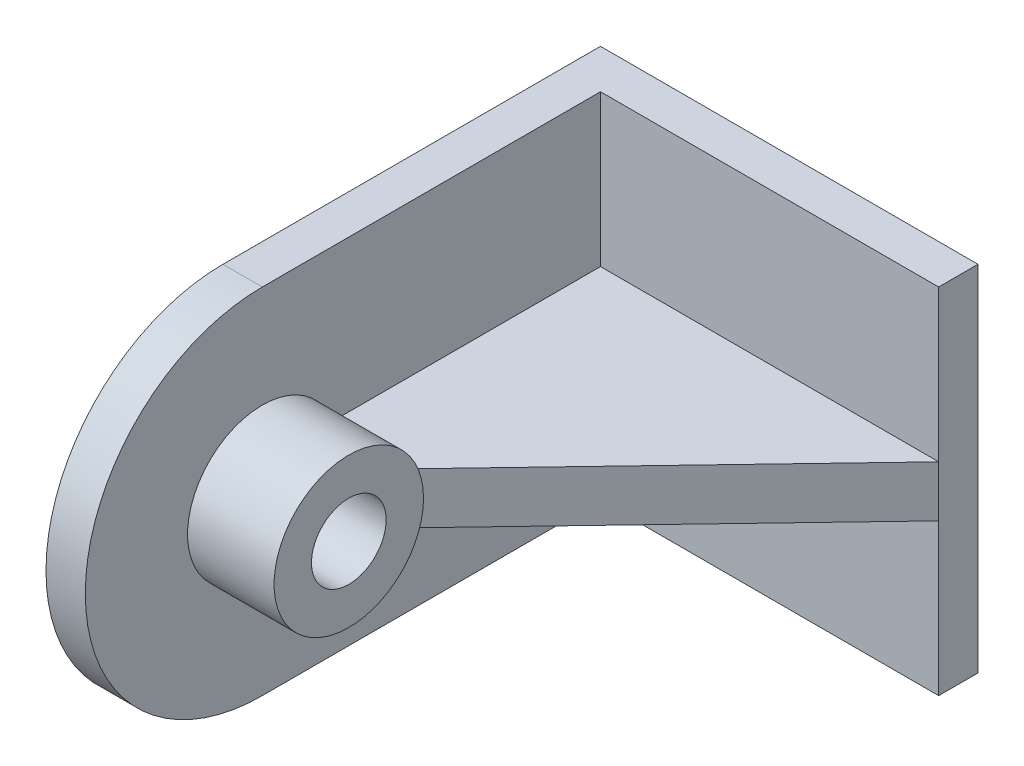
SolidWorks part; units mm, degrees
ref_plane "Front Plane" through (0, 0, 0) normal (1, 0, 0) x (0, 1, 0)
ref_plane "Top Plane" through (0, 0, 0) normal (0, 0, 1) x (0, 1, 0)
ref_plane "Right Plane" through (0, 0, 0) normal (0, 1, 0) x (-1, 0, 0)
sketch "Sketch1" plane through (0, 0, 0) normal (0, 0, 1) x (0, 1, 0)
  line L1 (-45, 48) -> (45, 48)
  line L2 (-45, 48) -> (-45, -48)
  line L3 (-45, -48) -> (45, -48)
  line L4 (45, 48) -> (45, -48)
  line L5 (-45, 48) -> (45, -48) construction
  line L6 (-45, -48) -> (45, 48) construction
  point P0 (0, 0)
  dimension "D1" = 90
  dimension "D2" = 96
extrude "Boss-Extrude1" add sketch "Sketch1" along normal blind 10
sketch "Sketch2" plane through (-48, 0, 0) normal (-1, 0, 0) x (0, -1, 0)
  line L0 (-45, 0) -> (-45, 96)
  line L1 (45, 96) -> (45, 0)
  line L2 (0, 0) -> (0, 84.8091) construction
  line L3 (-45, 0) -> (45, 0)
  arc A0 (-45, 96) -> (45, 96) centre (0, 96) cw
  dimension "D1" = 45
  dimension "D2" = 96
extrude "Boss-Extrude2" add sketch "Sketch2" against normal blind 10
sketch "Sketch3" plane through (-38, 0, 0) normal (1, 0, 0) x (0, 1, 0)
  circle A0 centre (0, 96) radius 19
  circle A1 centre (0, 96) radius 9.5
  dimension "D1" = 38
  dimension "D2" = 19
extrude "Boss-Extrude3" add sketch "Sketch3" along normal blind 22
sketch "Sketch4" plane through (0, 0, 0) normal (0, 1, 0) x (-1, 0, 0)
  line L0 (-48, 10) -> (16, 77)
rib "Rib1" sketch "Sketch4" sketch "Sketch4" thickness 13 extrusion direction parallel to sketch draft on no parameters "D1"=13
